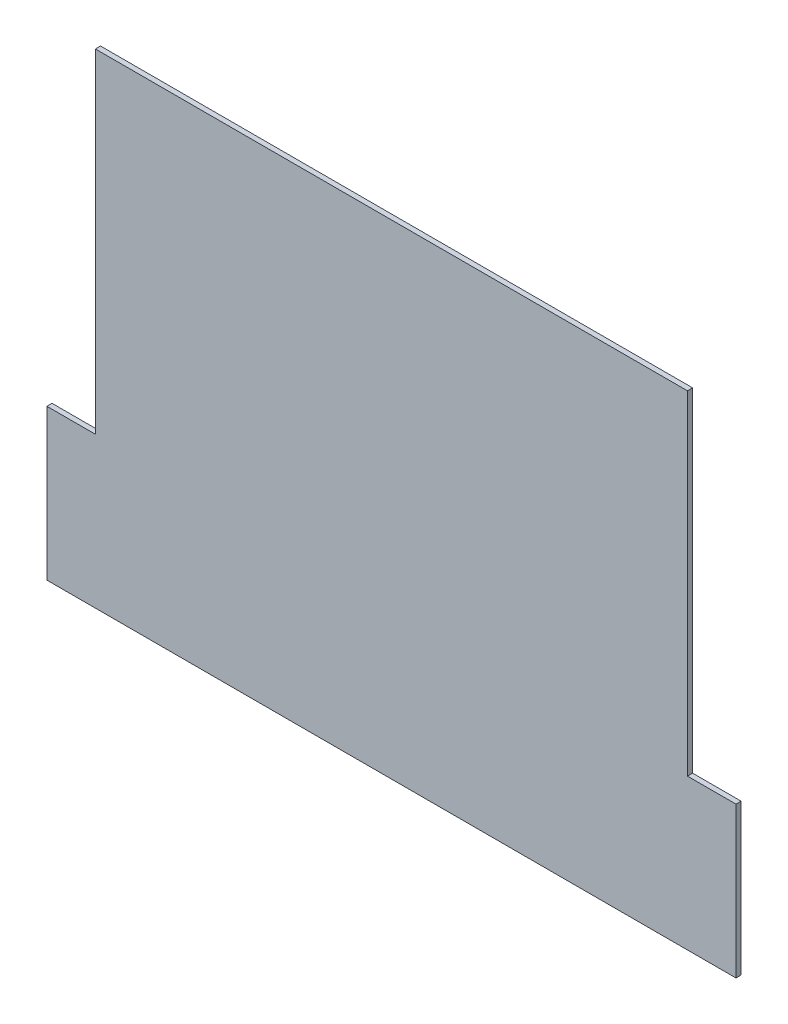
SolidWorks part; units mm, degrees
ref_plane "Front Plane" through (0, 0, 0) normal (0, 0, 1) x (1, 0, 0)
ref_plane "Top Plane" through (0, 0, 0) normal (0, 1, 0) x (1, 0, 0)
ref_plane "Right Plane" through (0, 0, 0) normal (1, 0, 0) x (0, 0, -1)
sketch "Sketch1" plane through (0, 0, 0) normal (0, 0, 1) x (1, 0, 0)
  line L1 (0, 0) -> (402.7, 0)
  line L2 (0, 0) -> (0, 88)
  line L3 (28.35, 283) -> (374.35, 283)
  line L4 (402.7, 0) -> (402.7, 88)
  line L7 (402.7, 88) -> (374.35, 88)
  line L8 (374.35, 283) -> (374.35, 88)
  line L11 (0, 88) -> (28.35, 88)
  line L12 (28.35, 283) -> (28.35, 88)
  dimension "D1" = 402.7
  dimension "D2" = 283
  dimension "D3" = 195
  dimension "D4" = 28.35
extrude "Boss-Extrude1" add sketch "Sketch1" along normal blind 3
